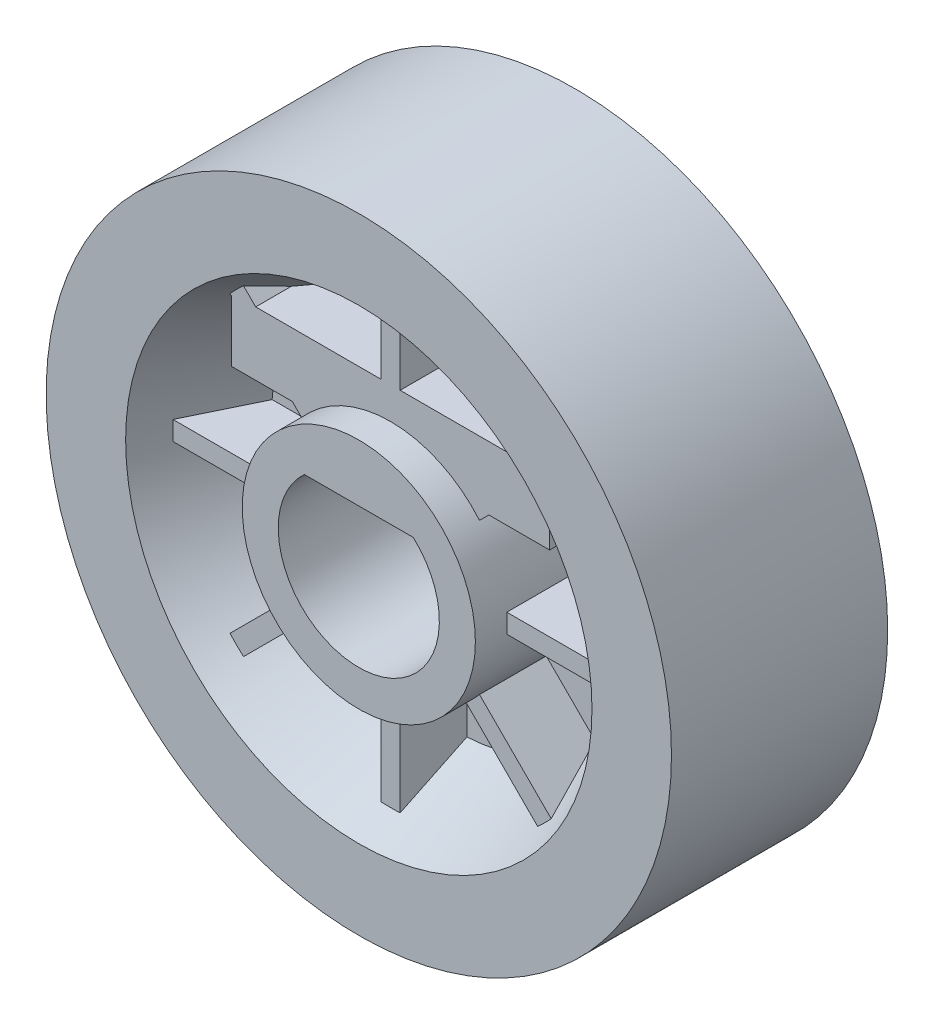
SolidWorks part; units mm, degrees
material "ABS"
ref_plane "Спереди" through (0, 0, 0) normal (0, 0, 1) x (1, 0, 0)
ref_plane "Сверху" through (0, 0, 0) normal (0, 1, 0) x (1, 0, 0)
ref_plane "Справа" through (0, 0, 0) normal (1, 0, 0) x (0, 0, -1)
sketch "Эскиз1" plane through (0, 0, 0) normal (0, 1, 0) x (1, 0, 0)
  line L0 (0, 0) -> (0, 15.044) construction
  line L1 (0, 0) -> (-5, 0) construction
  line L2 (-5, 0) -> (-11, 0)
  line L3 (-11, 0) -> (-11, 9.3)
  line L4 (-11, 9.3) -> (-17.5, 9.3)
  line L5 (-17.5, 9.3) -> (-22, 0)
  line L6 (-22, 0) -> (-29.5, 0)
  line L7 (-29.5, 0) -> (-29.5, 20.4)
  line L8 (-5, 0) -> (-5, 20.4)
  line L9 (-5, 10.2) -> (-29.5, 10.2) construction
  line L10 (-22, 20.4) -> (-29.5, 20.4)
  line L11 (-17.5, 11.1) -> (-22, 20.4)
  line L12 (-11, 11.1) -> (-17.5, 11.1)
  line L13 (-11, 20.4) -> (-11, 11.1)
  line L14 (-5, 20.4) -> (-11, 20.4)
  dimension "D1" = 10
  dimension "D2" = 22
  dimension "D3" = 35
  dimension "D4" = 59
  dimension "D5" = 44
  dimension "D6" = 10.2
  dimension "D7" = 9.3
revolve "Повернуть1" add sketch "Эскиз1" angle 360 about L0
sketch "Эскиз2" plane through (0, 0, 0) normal (0, 0, 1) x (1, 0, 0)
  line L0 (-5.1381, 5.6) -> (5.1381, 5.6)
  circle A0 centre (0, 0) radius 7.6
  circle M1 centre (0, 0) radius 5
  dimension "D1" = 15.2
  dimension "D2" = 13.2
extrude "Вырез-Вытянуть1" cut sketch "Эскиз2" against normal through all contours L0 A0 M1
ref_plane "Плоскость1" through (0, 0, -3) normal (0, 0, 1) x (1, 0, 0)
sketch "Эскиз3" plane through (0, 0, -3) normal (0, 0, 1) x (1, 0, 0)
  line L0 (0, 0) -> (0, 34) construction
  line L1 (5.0205, 6.2933) -> (6.2933, 5.0205)
  line L2 (-0.9, 8) -> (0.9, 8)
  line L3 (-0.9, 8) -> (-0.9, 26)
  line L4 (-0.9, 26) -> (0.9, 26)
  line L5 (0.9, 8) -> (0.9, 26)
  line L6 (-0.9, 8) -> (0.9, 26) construction
  line L7 (-0.9, 26) -> (0.9, 8) construction
  line L8 (5.0205, 6.2933) -> (17.7484, 19.0212)
  line L9 (17.7484, 19.0212) -> (19.0212, 17.7484)
  line L10 (6.2933, 5.0205) -> (19.0212, 17.7484)
  line L11 (5.0205, 6.2933) -> (19.0212, 17.7484) construction
  line L12 (17.7484, 19.0212) -> (6.2933, 5.0205) construction
  line L13 (8, 0.9) -> (8, -0.9)
  line L14 (8, 0.9) -> (26, 0.9)
  line L15 (26, 0.9) -> (26, -0.9)
  line L16 (8, -0.9) -> (26, -0.9)
  line L17 (8, 0.9) -> (26, -0.9) construction
  line L18 (26, 0.9) -> (8, -0.9) construction
  line L19 (6.2933, -5.0205) -> (5.0205, -6.2933)
  line L20 (6.2933, -5.0205) -> (19.0212, -17.7484)
  line L21 (19.0212, -17.7484) -> (17.7484, -19.0212)
  line L22 (5.0205, -6.2933) -> (17.7484, -19.0212)
  line L23 (6.2933, -5.0205) -> (17.7484, -19.0212) construction
  line L24 (19.0212, -17.7484) -> (5.0205, -6.2933) construction
  line L25 (0.9, -8) -> (-0.9, -8)
  line L26 (0.9, -8) -> (0.9, -26)
  line L27 (0.9, -26) -> (-0.9, -26)
  line L28 (-0.9, -8) -> (-0.9, -26)
  line L29 (0.9, -8) -> (-0.9, -26) construction
  line L30 (0.9, -26) -> (-0.9, -8) construction
  line L31 (-5.0205, -6.2933) -> (-6.2933, -5.0205)
  line L32 (-5.0205, -6.2933) -> (-17.7484, -19.0212)
  line L33 (-17.7484, -19.0212) -> (-19.0212, -17.7484)
  line L34 (-6.2933, -5.0205) -> (-19.0212, -17.7484)
  line L35 (-5.0205, -6.2933) -> (-19.0212, -17.7484) construction
  line L36 (-17.7484, -19.0212) -> (-6.2933, -5.0205) construction
  line L37 (-8, -0.9) -> (-8, 0.9)
  line L38 (-8, -0.9) -> (-26, -0.9)
  line L39 (-26, -0.9) -> (-26, 0.9)
  line L40 (-8, 0.9) -> (-26, 0.9)
  line L41 (-8, -0.9) -> (-26, 0.9) construction
  line L42 (-26, -0.9) -> (-8, 0.9) construction
  line L43 (-6.2933, 5.0205) -> (-5.0205, 6.2933)
  line L44 (-6.2933, 5.0205) -> (-19.0212, 17.7484)
  line L45 (-19.0212, 17.7484) -> (-17.7484, 19.0212)
  line L46 (-5.0205, 6.2933) -> (-17.7484, 19.0212)
  line L47 (-6.2933, 5.0205) -> (-17.7484, 19.0212) construction
  line L48 (-19.0212, 17.7484) -> (-5.0205, 6.2933) construction
  point P6 (0, 17)
  point P11 (12.0208, 12.0208)
  point P16 (17, 0)
  point P21 (12.0208, -12.0208)
  point P26 (0, -17)
  point P31 (-12.0208, -12.0208)
  point P36 (-17, 0)
  point P41 (-12.0208, 12.0208)
  point P46 (0, 0)
  dimension "D1" = 1.8
  dimension "D2" = 8
  dimension "D3" = 8
extrude "Бобышка-Вытянуть1" add sketch "Эскиз3" against normal blind 15
sketch "Эскиз4" plane through (0, 0, -3) normal (0, 0, 1) x (1, 0, 0)
  line L0 (0, 0) -> (0, 11) construction
  line L2 (15, 8) -> (-15, 8)
  line L3 (15, 8) -> (15, 14)
  line L4 (15, 14) -> (-15, 14)
  line L5 (-15, 8) -> (-15, 14)
  line L6 (15, 8) -> (-15, 14) construction
  line L7 (15, 14) -> (-15, 8) construction
  arc A0 (0.9, 10.9631) -> (-0.9, 10.9631) centre (0, 0) ccw construction
  dimension "D1" = 6
  dimension "D2" = 30
extrude "Бобышка-Вытянуть2" add sketch "Эскиз4" against normal blind 15
scale "Масштаб1" scale about centroid uniform scaling yes scale factor 1.01
